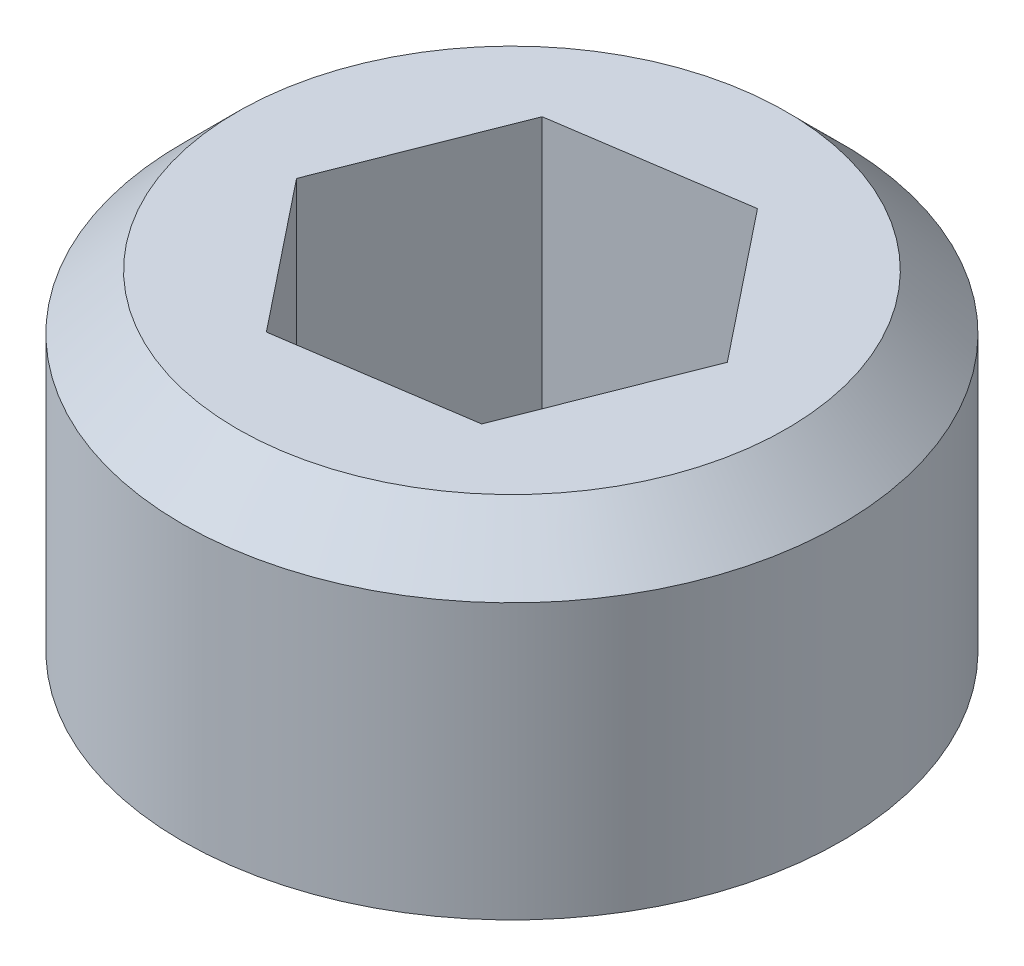
SolidWorks part; units mm, degrees
ref_plane "前视基准面" through (0, 0, 0) normal (0, 0, 1) x (1, 0, 0)
ref_plane "上视基准面" through (0, 0, 0) normal (0, 1, 0) x (1, 0, 0)
ref_plane "右视基准面" through (0, 0, 0) normal (1, 0, 0) x (0, 0, -1)
sketch "草图1" plane through (0, 0, 0) normal (0, 1, 0) x (1, 0, 0)
  circle A0 centre (0, 0) radius 6
  dimension "D1" = 12
extrude "凸台-拉伸1" add sketch "草图1" along normal blind 6
sketch "草图2" plane through (0, 6, 0) normal (0, 1, 0) x (1, 0, 0)
  line L1 (1.2615, 3.2087) -> (-2.148, 2.6969)
  line L2 (-2.148, 2.6969) -> (-3.4096, -0.5118)
  line L3 (-3.4096, -0.5118) -> (-1.2615, -3.2087)
  line L4 (-1.2615, -3.2087) -> (2.148, -2.6969)
  line L5 (2.148, -2.6969) -> (3.4096, 0.5118)
  line L6 (3.4096, 0.5118) -> (1.2615, 3.2087)
  circle A0 centre (0, 0) radius 2.9859 construction
extrude "切除-拉伸1" cut sketch "草图2" against normal blind 5
chamfer "倒角1" distance 1 angle 45 1 edges at (0, 6, 6)
